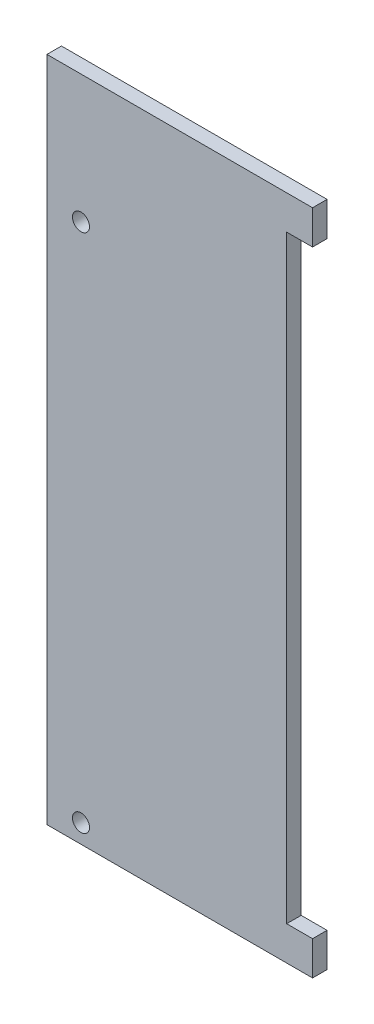
SolidWorks part; units mm, degrees
ref_plane "Front Plane" through (0, 0, 0) normal (0, 0, 1) x (1, 0, 0)
ref_plane "Top Plane" through (0, 0, 0) normal (0, 1, 0) x (1, 0, 0)
ref_plane "Right Plane" through (0, 0, 0) normal (1, 0, 0) x (0, 0, -1)
sketch "Sketch1" plane through (0, 0, 0) normal (0, 0, 1) x (1, 0, 0)
  line L0 (49.53, 111.6889) -> (39.878, 111.6889)
  line L1 (-49.53, -124.3889) -> (49.53, -124.3889)
  line L2 (-49.53, -124.3889) -> (-49.53, 124.3889)
  line L3 (-49.53, 124.3889) -> (49.53, 124.3889)
  line L4 (49.53, -124.3889) -> (49.53, 124.3889)
  line L5 (-49.53, -124.3889) -> (49.53, 124.3889) construction
  line L6 (-49.53, 124.3889) -> (49.53, -124.3889) construction
  line L7 (39.878, 111.6889) -> (39.878, -111.6889)
  line L8 (39.878, -111.6889) -> (49.53, -111.6889)
  line L9 (49.53, 111.5365) -> (40.0304, 111.5365) construction
  line L10 (40.0304, 111.5365) -> (40.0304, -111.5365) construction
  line L11 (40.0304, -111.5365) -> (49.53, -111.5365) construction
  circle A0 centre (-36.83, -117.4039) radius 3.175
  circle A1 centre (-36.83, 76.6369) radius 3.175
  point P0 (0, 0)
  dimension "D3" = 12.7
  dimension "D2" = 194.0408
  dimension "D1" = 99.06
  dimension "D4" = 6.985
  dimension "D5" = 47.752
  dimension "D6" = 12.7
  dimension "D7" = 9.652
  dimension "D8" = 12.7
  dimension "D9" = 12.7
  dimension "D10" = 0.1524
extrude "Boss-Extrude1" add sketch "Sketch1" along normal blind 5.4102 contours L8 L7 L0 L4 L3 L2 L1 A1 A0
